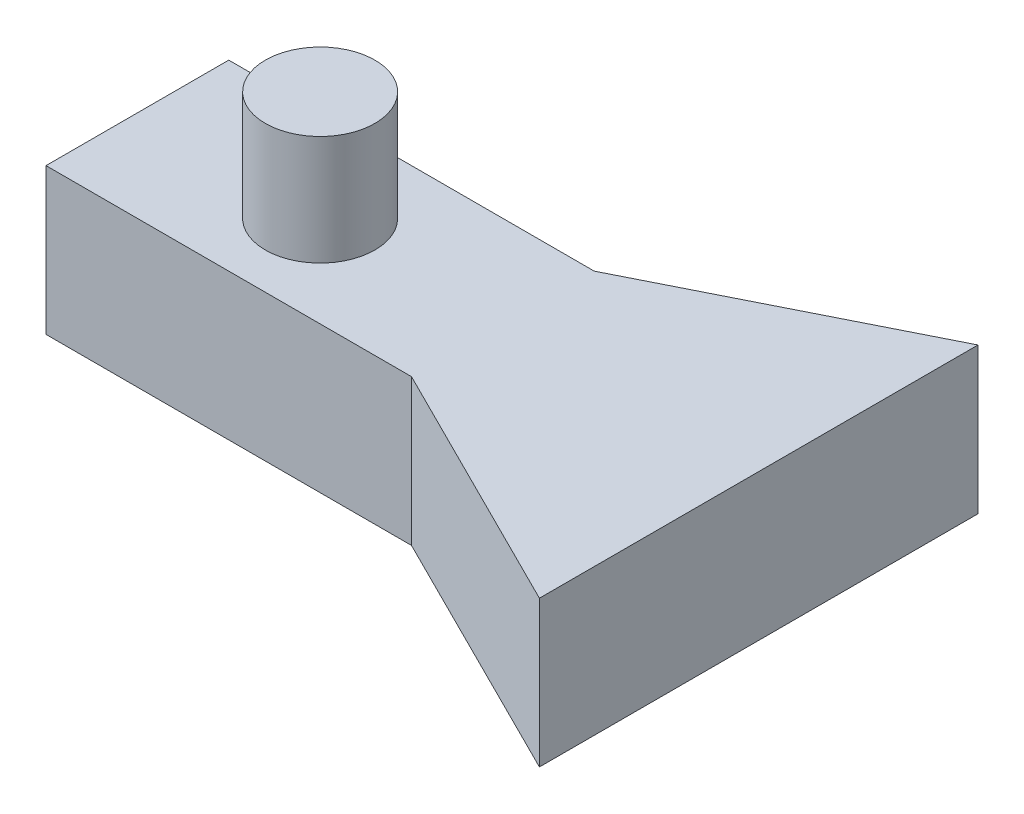
SolidWorks part; units mm, degrees
ref_plane "Front Plane" through (0, 0, 0) normal (0, 0, 1) x (1, 0, 0)
ref_plane "Top Plane" through (0, 0, 0) normal (0, 1, 0) x (1, 0, 0)
ref_plane "Right Plane" through (0, 0, 0) normal (1, 0, 0) x (0, 0, -1)
sketch "Sketch1" plane through (0, 0, 0) normal (0, 1, 0) x (1, 0, 0)
  line L0 (1000, 500) -> (1700, 850)
  line L1 (0, 0) -> (1000, 0)
  line L2 (0, 0) -> (0, 500)
  line L3 (0, 500) -> (1000, 500)
  line L4 (1000, 0) -> (1000, 500)
  line L5 (1700, 850) -> (1700, -350)
  line L6 (1700, -350) -> (1000, 0)
  line L7 (0, 0) -> (1000, 500) construction
  line L8 (0, 500) -> (1000, 0) construction
  dimension "D1" = 1000
  dimension "D2" = 500
  dimension "D3" = 700
extrude "Boss-Extrude1" add sketch "Sketch1" along normal blind 400 contours L6 L5 L0 L4 | L1 L4 L3 L2
sketch "Sketch2" plane through (0, 400, 0) normal (0, 1, 0) x (1, 0, 0)
  line L0 (0, 0) -> (1000, 500) construction
  line L1 (0, 500) -> (1000, 0) construction
  circle A0 centre (500, 250) radius 150
  dimension "D1" = 300
extrude "Boss-Extrude2" add sketch "Sketch2" along normal blind 300
